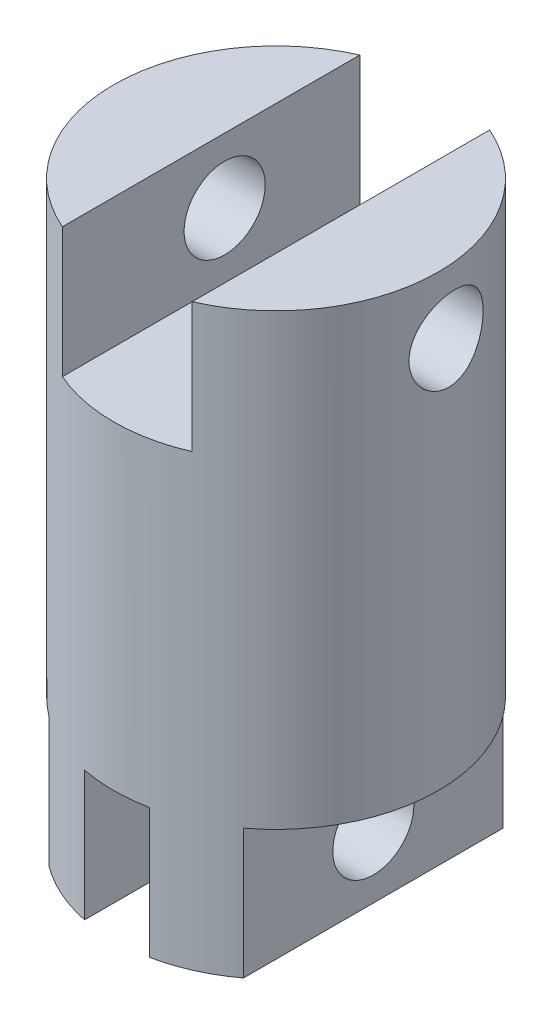
SolidWorks part; units mm, degrees
ref_plane "Front Plane" through (0, 0, 0) normal (0, 0, 1) x (1, 0, 0)
ref_plane "Top Plane" through (0, 0, 0) normal (0, 1, 0) x (1, 0, 0)
ref_plane "Right Plane" through (0, 0, 0) normal (1, 0, 0) x (0, 0, -1)
sketch "Sketch1" plane through (0, 0, 0) normal (0, 1, 0) x (1, 0, 0)
  circle A0 centre (0, 0) radius 12.7
  dimension "D1" = 25.4
extrude "Boss-Extrude1" add sketch "Sketch1" along normal blind 45.3136
sketch "Sketch2" plane through (0, 45.3136, 0) normal (0, 1, 0) x (1, 0, 0)
  line L0 (5.08, 11.6397) -> (5.08, -11.6397)
  line L1 (-5.08, 11.6397) -> (-5.08, -11.6397)
  arc A0 (-5.08, -11.6397) -> (5.08, -11.6397) centre (0, 0) ccw
  arc A1 (5.08, 11.6397) -> (-5.08, 11.6397) centre (0, 0) ccw
  dimension "D2" = 25.4
  dimension "D1" = 5.08
  dimension "D3" = 5.08
extrude "Cut-Extrude1" cut sketch "Sketch2" against normal blind 10.16
sketch "Sketch3" plane through (0, 0, 0) normal (0, -1, 0) x (1, 0, 0)
  line L0 (-2.54, 12.4434) -> (-2.54, -12.4434)
  line L1 (-7.62, 10.16) -> (-7.62, -10.16)
  line L2 (2.54, 12.4434) -> (2.54, -12.4434)
  line L3 (7.62, 10.16) -> (7.62, -10.16)
  arc A0 (-7.62, 10.16) -> (-7.62, -10.16) centre (0, 0) ccw
  arc A1 (-2.54, -12.4434) -> (2.54, -12.4434) centre (0, 0) ccw
  arc A2 (7.62, -10.16) -> (7.62, 10.16) centre (0, 0) ccw
  arc A3 (2.54, 12.4434) -> (-2.54, 12.4434) centre (0, 0) ccw
  dimension "D1" = 25.4
  dimension "D2" = 2.54
  dimension "D3" = 5.08
  dimension "D4" = 2.54
  dimension "D5" = 5.08
extrude "Cut-Extrude2" cut sketch "Sketch3" against normal blind 10.16
sketch "Sketch4" plane through (-5.08, 0, 0) normal (1, 0, 0) x (0, 0, -1)
  line L0 (11.6397, 45.3136) -> (-11.6397, 45.3136) construction
  line L5 (10.16, 0) -> (-10.16, 0) construction
  circle A0 centre (1.0603, 40.2336) radius 3.175
  circle A2 centre (0, 5.08) radius 3.175
  point P7 (-7.1225, 36.195)
  dimension "D1" = 6.35
  dimension "D3" = 6.35
  dimension "D2" = 5.08
  dimension "D4" = 5.08
extrude "Cut-Extrude3" cut sketch "Sketch4" against normal through all both and the other way through all
sketch "Sketch5" plane through (0, 35.1536, 0) normal (0, 1, 0) x (1, 0, 0)
  circle A0 centre (0, 0) radius 2.54
  dimension "D1" = 5.08
extrude "Cut-Extrude4" cut sketch "Sketch5" against normal through all
